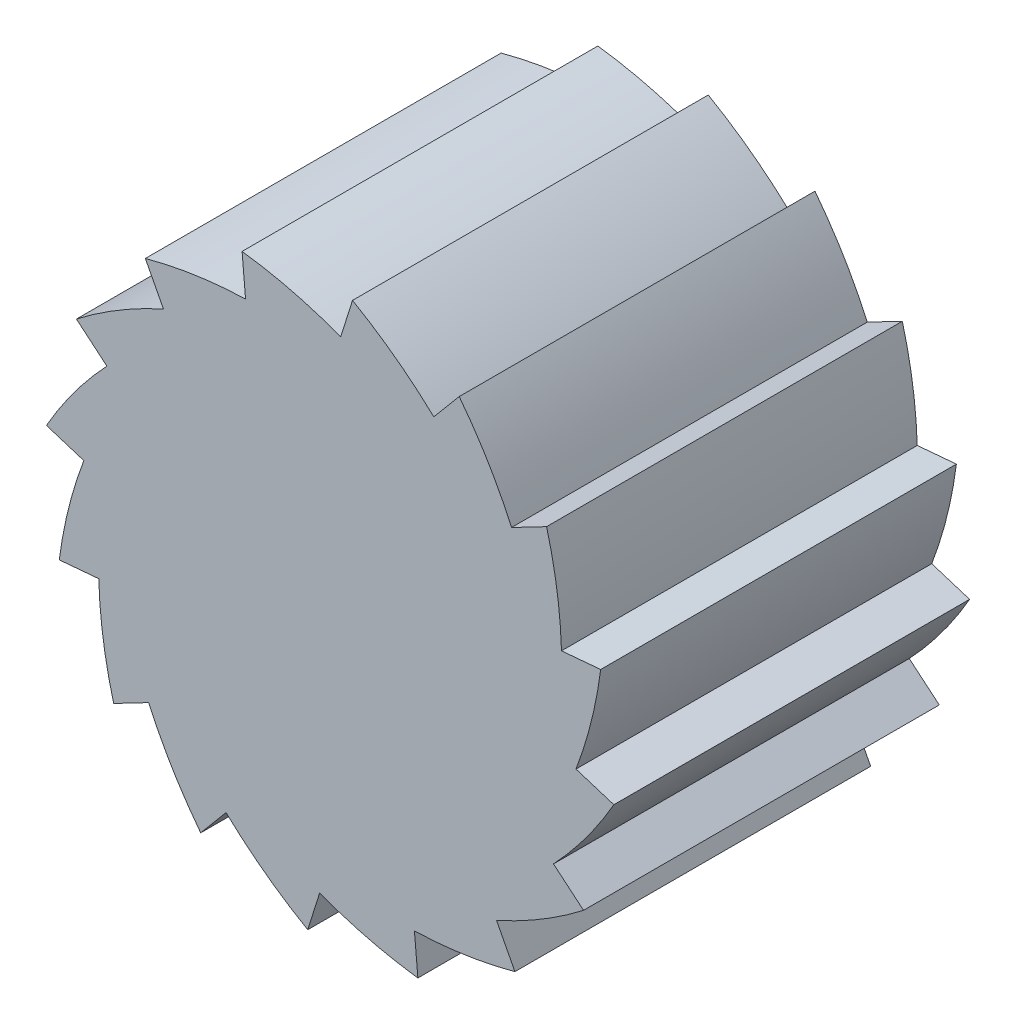
SolidWorks part; units mm, degrees
ref_plane "Front Plane" through (0, 0, 0) normal (0, 0, 1) x (1, 0, 0)
ref_plane "Top Plane" through (0, 0, 0) normal (0, 1, 0) x (1, 0, 0)
ref_plane "Right Plane" through (0, 0, 0) normal (1, 0, 0) x (0, 0, -1)
sketch "Sketch1" plane through (0, 0, 0) normal (0, 0, 1) x (1, 0, 0)
  line L8 (3.2611, 1.194) -> (3.8117, 1.2424)
  line L9 (3.1487, -1.4556) -> (3.5709, -1.8096)
  line L10 (1.1943, -3.2481) -> (1.2425, -3.7974)
  line L11 (-1.4536, -3.1321) -> (-1.8095, -3.5565)
  line L12 (-3.2425, -1.1795) -> (-3.7972, -1.2282)
  line L13 (-3.1284, 1.4648) -> (-3.5564, 1.8238)
  line L14 (-1.1792, 3.2555) -> (-1.228, 3.8116)
  line L15 (1.4668, 3.1449) -> (1.8239, 3.5708)
  line L16 (3.4648, -0.1432) -> (3.997, -0.3109)
  line L17 (2.3484, -2.5429) -> (2.6066, -3.0384)
  line L18 (-0.1379, -3.4524) -> (-0.3053, -3.9838)
  line L19 (-2.5413, -2.3373) -> (-3.0328, -2.5934)
  line L20 (-3.4521, 0.1527) -> (-3.9782, 0.3185)
  line L21 (-2.3332, 2.5574) -> (-2.5878, 3.046)
  line L22 (0.1581, 3.4644) -> (0.3241, 3.9914)
  line L23 (2.559, 2.3443) -> (3.0516, 2.601)
  arc A10 (3.8117, 1.2424) -> (3.4648, -0.1432) centre (-2.2135, 2.0148) cw
  arc A11 (3.5709, -1.8096) -> (2.3484, -2.5429) centre (-0.1434, 2.997) cw
  arc A12 (1.2425, -3.7974) -> (-0.1379, -3.4524) centre (2.0149, 2.2278) cw
  arc A13 (-1.8095, -3.5565) -> (-2.5413, -2.3373) centre (2.9971, 0.1577) cw
  arc A14 (-3.7972, -1.2282) -> (-3.4521, 0.1527) centre (2.2279, -2.0006) cw
  arc A15 (-3.5564, 1.8238) -> (-2.3332, 2.5574) centre (0.1579, -2.9828) cw
  arc A16 (-1.228, 3.8116) -> (0.1581, 3.4644) centre (-2.0004, -2.2136) cw
  arc A17 (1.8239, 3.5708) -> (2.559, 2.3443) centre (-2.9827, -0.1435) cw
  arc A18 (3.997, -0.3109) -> (3.1487, -1.4556) centre (-1.2739, 2.7085) cw
  arc A19 (2.6066, -3.0384) -> (1.1943, -3.2481) centre (1.0144, 2.8238) cw
  arc A20 (-0.3053, -3.9838) -> (-1.4536, -3.1321) centre (2.7141, 1.2871) cw
  arc A21 (-3.0328, -2.5934) -> (-3.2425, -1.1795) centre (2.8294, -1.0012) cw
  arc A22 (-3.9782, 0.3185) -> (-3.1284, 1.4648) centre (1.2927, -2.7009) cw
  arc A23 (-2.5878, 3.046) -> (-1.1792, 3.2555) centre (-0.9956, -2.8162) cw
  arc A24 (0.3241, 3.9914) -> (1.4668, 3.1449) centre (-2.6953, -1.2795) cw
  arc A25 (3.0516, 2.601) -> (3.2611, 1.194) centre (-2.8106, 1.0088) cw
  point P50 (0, 0)
  dimension "D1" = 2
extrude "Boss-Extrude3" add sketch "Sketch1" along normal blind 5
